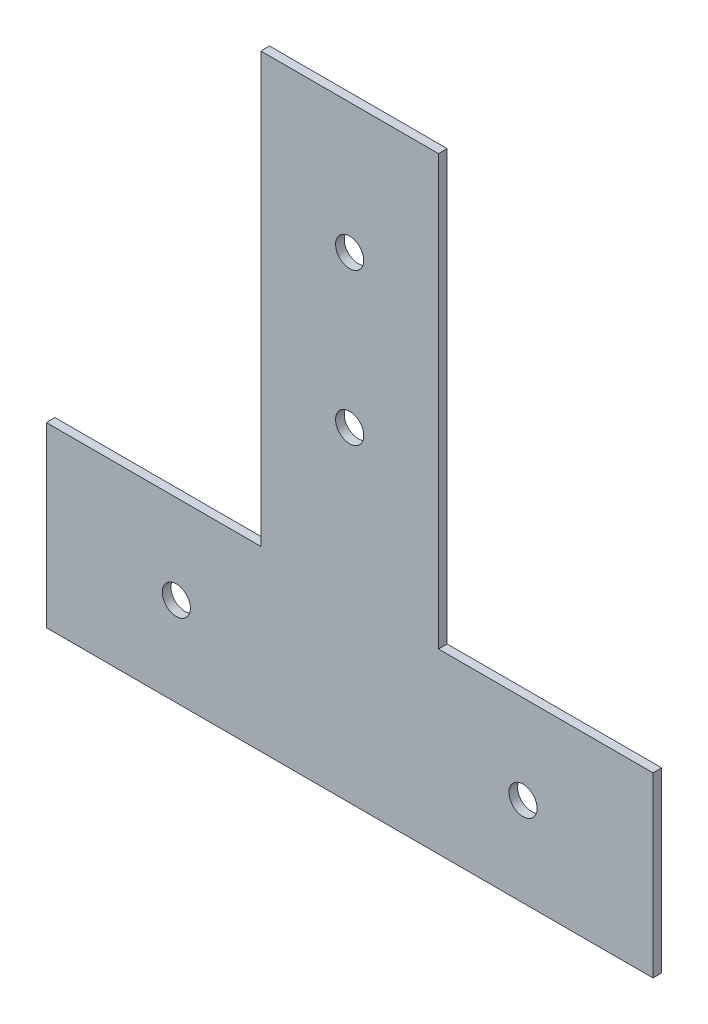
SolidWorks part; units mm, degrees
ref_plane "前视基准面" through (0, 0, 0) normal (0, 0, 1) x (1, 0, 0)
ref_plane "上视基准面" through (0, 0, 0) normal (0, 1, 0) x (1, 0, 0)
ref_plane "右视基准面" through (0, 0, 0) normal (1, 0, 0) x (0, 0, -1)
sketch "草图1" plane through (0, 0, 0) normal (0, 0, 1) x (1, 0, 0)
  line L1 (-70, -20.5) -> (70, -20.5)
  line L2 (-70, -20.5) -> (-70, 20.5)
  line L3 (-70, 20.5) -> (-20.5, 20.5)
  line L4 (70, -20.5) -> (70, 20.5)
  line L5 (-70, -20.5) -> (70, 20.5) construction
  line L6 (-70, 20.5) -> (70, -20.5) construction
  line L9 (-20.5, 119.5) -> (20.5, 119.5)
  line L10 (20.5, 20.5) -> (70, 20.5)
  line L11 (-20.5, 20.5) -> (-20.5, 119.5)
  line L12 (20.5, 20.5) -> (20.5, 119.5)
  point P0 (0, 0)
  point P6 (0, 119.5)
  dimension "D1" = 41
  dimension "D2" = 140
  dimension "D3" = 41
  dimension "D4" = 140
extrude "凸台-拉伸1" add sketch "草图1" along normal blind 2
sketch "草图2" plane through (0, 0, 2) normal (0, 0, 1) x (1, 0, 0)
  line L0 (0, 0) -> (0, 16.8919) construction
  line L2 (-70, 20.5) -> (-70, -20.5) construction
  line L3 (20.5, 119.5) -> (-20.5, 119.5) construction
  circle A0 centre (0, 89.5) radius 3.25
  circle A1 centre (0, 54.5) radius 3.25
  circle A2 centre (-40, 0) radius 3.25
  circle A3 centre (40, 0) radius 3.25
  dimension "D1" = 6.5
  dimension "D2" = 6.5
  dimension "D3" = 6.5
  dimension "D4" = 30
  dimension "D5" = 35
  dimension "D6" = 30
extrude "切除-拉伸1" cut sketch "草图2" against normal through all
